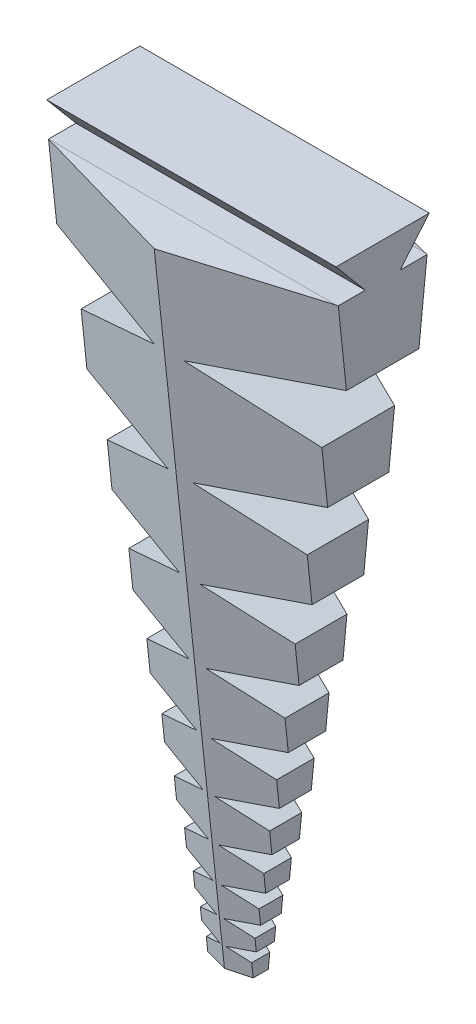
SolidWorks part; units mm, degrees
ref_plane "Front Plane" through (0, 0, 0) normal (0, 0, 1) x (1, 0, 0)
ref_plane "Top Plane" through (0, 0, 0) normal (0, 1, 0) x (1, 0, 0)
ref_plane "Right Plane" through (0, 0, 0) normal (1, 0, 0) x (0, 0, -1)
sketch "spiral_flat" plane through (0, 0, 0) normal (0, 0, 1) x (1, 0, 0)
  line L0 (3.2655, 0) -> (-3.2655, 0) construction
  line L1 (3.9293, 3.054) -> (-3.9293, 3.054) construction
  line L2 (4.728, 6.7288) -> (-4.728, 6.7288) construction
  line L3 (5.689, 11.1506) -> (-5.689, 11.1506) construction
  line L4 (6.8455, 16.4712) -> (-6.8455, 16.4712) construction
  line L5 (8.2369, 22.8733) -> (-8.2369, 22.8733) construction
  line L6 (9.9112, 30.5768) -> (-9.9112, 30.5768) construction
  line L7 (11.9259, 39.8461) -> (-11.9259, 39.8461) construction
  line L8 (14.35, 50.9996) -> (-14.35, 50.9996) construction
  line L9 (17.2669, 64.4202) -> (-17.2669, 64.4202) construction
  line L10 (20.7767, 80.5689) -> (-20.7767, 80.5689) construction
  line L11 (25, 100) -> (-25, 100) construction
  line L12 (0, -2.9617) -> (0, 103.8438) construction
  line L13 (3.2655, 0) -> (25, 100) construction
  line L14 (-3.2655, 0) -> (-25, 100) construction
  line L15 (0.3266, 0) -> (2.5, 100) construction
  line L16 (-0.3266, 0) -> (-2.5, 100) construction
  line L17 (-20.7767, 80.5689) -> (-20.7767, 100) construction
  line L18 (-17.2669, 64.4202) -> (-17.2669, 80.5689) construction
  line L19 (-14.35, 50.9996) -> (-14.35, 64.4202) construction
  line L20 (-11.9259, 39.8461) -> (-11.9259, 50.9996) construction
  line L21 (-9.9112, 30.5768) -> (-9.9112, 39.8461) construction
  line L22 (-8.2369, 22.8733) -> (-8.2369, 30.5768) construction
  line L23 (-6.8455, 16.4712) -> (-6.8455, 22.8733) construction
  line L24 (-5.689, 11.1506) -> (-5.689, 16.4712) construction
  line L25 (-4.728, 6.7288) -> (-4.728, 11.1506) construction
  line L26 (-3.9293, 3.054) -> (-3.9293, 6.7288) construction
  line L27 (-3.2655, 0) -> (-3.2655, 3.054) construction
  line L28 (20.7767, 80.5689) -> (20.7767, 100) construction
  line L29 (14.35, 50.9996) -> (14.35, 64.4202) construction
  line L30 (17.2669, 64.4202) -> (17.2669, 80.5689) construction
  line L31 (11.9259, 39.8461) -> (11.9259, 50.9996) construction
  line L32 (9.9112, 30.5768) -> (9.9112, 39.8461) construction
  line L33 (8.2369, 22.8733) -> (8.2369, 30.5768) construction
  line L34 (6.8455, 16.4712) -> (6.8455, 22.8733) construction
  line L35 (5.689, 11.1506) -> (5.689, 16.4712) construction
  line L36 (4.728, 6.7288) -> (4.728, 11.1506) construction
  line L37 (3.9293, 3.054) -> (3.9293, 6.7288) construction
  line L38 (3.2655, 0) -> (3.2655, 3.054) construction
  line L39 (-2.0777, 80.5689) -> (-17.2669, 75.0404) construction
  line L40 (-1.7267, 64.4202) -> (-17.2669, 67.1604) construction
  line L41 (-2.0777, 80.5689) -> (-20.7767, 83.866) construction
  line L42 (-1.7267, 64.4202) -> (-14.35, 59.8257) construction
  line L43 (-1.435, 50.9996) -> (-14.35, 53.2769) construction
  line L44 (-1.435, 50.9996) -> (-11.9259, 47.1812) construction
  line L45 (-1.1926, 39.8461) -> (-11.9259, 41.7387) construction
  line L46 (-1.1926, 39.8461) -> (-9.9112, 36.6728) construction
  line L47 (-0.9911, 30.5768) -> (-9.9112, 32.1496) construction
  line L48 (-0.9911, 30.5768) -> (-8.2369, 27.9395) construction
  line L49 (-0.8237, 22.8733) -> (-8.2369, 24.1805) construction
  line L50 (-0.8237, 22.8733) -> (-6.8455, 20.6816) construction
  line L51 (-0.6845, 16.4712) -> (-6.8455, 17.5576) construction
  line L52 (-0.6845, 16.4712) -> (-5.689, 14.6497) construction
  line L53 (-0.5689, 11.1506) -> (-5.689, 12.0534) construction
  line L54 (-0.5689, 11.1506) -> (-4.728, 9.6368) construction
  line L55 (-0.4728, 6.7288) -> (-4.728, 7.4791) construction
  line L56 (-0.4728, 6.7288) -> (-3.9293, 5.4708) construction
  line L57 (-0.3929, 3.054) -> (-3.9293, 3.6776) construction
  line L58 (-0.3929, 3.054) -> (-3.2655, 2.0085) construction
  line L59 (0.3929, 3.054) -> (3.2655, 2.0085) construction
  line L60 (0.3929, 3.054) -> (3.9293, 3.6776) construction
  line L61 (0.4728, 6.7288) -> (3.9293, 5.4708) construction
  line L62 (0.4728, 6.7288) -> (4.728, 7.4791) construction
  line L63 (0.5689, 11.1506) -> (4.728, 9.6368) construction
  line L64 (0.5689, 11.1506) -> (5.689, 12.0534) construction
  line L65 (0.6845, 16.4712) -> (5.689, 14.6497) construction
  line L66 (0.6845, 16.4712) -> (6.8455, 17.5576) construction
  line L67 (0.8237, 22.8733) -> (6.8455, 20.6816) construction
  line L68 (0.8237, 22.8733) -> (8.2369, 24.1805) construction
  line L69 (0.9911, 30.5768) -> (8.2369, 27.9395) construction
  line L70 (0.9911, 30.5768) -> (9.9112, 32.1496) construction
  line L71 (1.1926, 39.8461) -> (9.9112, 36.6728) construction
  line L72 (1.1926, 39.8461) -> (11.9259, 41.7387) construction
  line L73 (1.435, 50.9996) -> (11.9259, 47.1812) construction
  line L74 (1.435, 50.9996) -> (14.35, 53.2769) construction
  line L75 (1.7267, 64.4202) -> (14.35, 59.8257) construction
  line L76 (1.7267, 64.4202) -> (17.2669, 67.1604) construction
  line L77 (2.0777, 80.5689) -> (17.2669, 75.0404) construction
  line L78 (2.0777, 80.5689) -> (20.7767, 83.866) construction
  line L143 (-20.7767, 100) -> (-25, 100)
  line L144 (-25, 100) -> (-3.2655, 0)
  line L145 (-3.2655, 0) -> (-3.2655, 2.0085)
  line L146 (-0.3929, 3.054) -> (-3.9293, 3.6776)
  line L147 (-3.9293, 5.4708) -> (-0.4728, 6.7288)
  line L148 (-4.728, 7.4791) -> (-4.728, 9.6368)
  line L149 (-0.5689, 11.1506) -> (-5.689, 12.0534)
  line L150 (-5.689, 14.6497) -> (-0.6845, 16.4712)
  line L151 (-6.8455, 17.5576) -> (-6.8455, 20.6816)
  line L152 (-0.8237, 22.8733) -> (-8.2369, 24.1805)
  line L153 (-9.9112, 36.6728) -> (-1.1926, 39.8461)
  line L154 (-1.1926, 39.8461) -> (-11.9259, 41.7387)
  line L155 (-14.35, 59.8257) -> (-1.7267, 64.4202)
  line L156 (-1.7267, 64.4202) -> (-17.2669, 67.1604)
  line L157 (-17.2669, 75.0404) -> (-2.0777, 80.5689)
  line L158 (-20.7767, 83.866) -> (-20.7767, 100)
  line L159 (3.2655, 2.0085) -> (3.2655, 0)
  line L160 (0.3929, 3.054) -> (3.2655, 2.0085)
  line L161 (3.9293, 3.6776) -> (0.3929, 3.054)
  line L162 (3.9293, 5.4708) -> (3.9293, 3.6776)
  line L163 (0.4728, 6.7288) -> (3.9293, 5.4708)
  line L164 (4.728, 7.4791) -> (0.4728, 6.7288)
  line L165 (4.728, 9.6368) -> (4.728, 7.4791)
  line L166 (0.5689, 11.1506) -> (4.728, 9.6368)
  line L167 (5.689, 12.0534) -> (0.5689, 11.1506)
  line L168 (5.689, 14.6497) -> (5.689, 12.0534)
  line L169 (0.6845, 16.4712) -> (5.689, 14.6497)
  line L170 (6.8455, 17.5576) -> (0.6845, 16.4712)
  line L171 (6.8455, 20.6816) -> (6.8455, 17.5576)
  line L172 (0.8237, 22.8733) -> (6.8455, 20.6816)
  line L173 (8.2369, 24.1805) -> (0.8237, 22.8733)
  line L174 (8.2369, 27.9395) -> (8.2369, 24.1805)
  line L175 (0.9911, 30.5768) -> (8.2369, 27.9395)
  line L176 (9.9112, 32.1496) -> (0.9911, 30.5768)
  line L177 (9.9112, 36.6728) -> (9.9112, 32.1496)
  line L178 (1.1926, 39.8461) -> (9.9112, 36.6728)
  line L179 (11.9259, 41.7387) -> (1.1926, 39.8461)
  line L180 (11.9259, 47.1812) -> (11.9259, 41.7387)
  line L181 (1.435, 50.9996) -> (11.9259, 47.1812)
  line L182 (14.35, 53.2769) -> (1.435, 50.9996)
  line L183 (14.35, 59.8257) -> (14.35, 53.2769)
  line L184 (1.7267, 64.4202) -> (14.35, 59.8257)
  line L185 (17.2669, 67.1604) -> (1.7267, 64.4202)
  line L186 (17.2669, 75.0404) -> (17.2669, 67.1604)
  line L187 (2.0777, 80.5689) -> (17.2669, 75.0404)
  line L188 (20.7767, 83.866) -> (2.0777, 80.5689)
  line L189 (20.7767, 100) -> (20.7767, 83.866)
  line L190 (25, 100) -> (3.2655, 0)
  line L191 (20.7767, 100) -> (25, 100)
  line L192 (-20.7767, 83.866) -> (-2.0777, 80.5689)
  line L193 (-17.2669, 75.0404) -> (-17.2669, 67.1604)
  line L194 (-14.35, 59.8257) -> (-14.35, 53.2769)
  line L195 (-14.35, 53.2769) -> (-1.435, 50.9996)
  line L196 (-1.435, 50.9996) -> (-11.9259, 47.1812)
  line L197 (-11.9259, 47.1812) -> (-11.9259, 41.7387)
  line L198 (-9.9112, 36.6728) -> (-9.9112, 32.1496)
  line L199 (-9.9112, 32.1496) -> (-0.9911, 30.5768)
  line L200 (-0.9911, 30.5768) -> (-8.2369, 27.9395)
  line L201 (-8.2369, 27.9395) -> (-8.2369, 24.1805)
  line L202 (-6.8455, 20.6816) -> (-0.8237, 22.8733)
  line L203 (-6.8455, 17.5576) -> (-0.6845, 16.4712)
  line L204 (-5.689, 14.6497) -> (-5.689, 12.0534)
  line L205 (-0.5689, 11.1506) -> (-4.728, 9.6368)
  line L206 (-4.728, 7.4791) -> (-0.4728, 6.7288)
  line L207 (-3.9293, 5.4708) -> (-3.9293, 3.6776)
  line L208 (-0.3929, 3.054) -> (-3.2655, 2.0085)
  spline S0 degree 3 poles (0, 0) (0, 1.018) (0, 3.261) (0, 6.9778) (0, 11.4502) (0, 16.8317) (0, 23.3071) (0, 31.0987) (0, 40.4742) (0, 51.7553) (0, 65.3296) (0, 81.663) (0, 93.523) (0, 100) knots 0 0 0 0 0.03054 0.067288 0.111506 0.164712 0.228733 0.305768 0.398461 0.509996 0.644202 0.805689 1 1 1 1
  point P39 (0, 3.054)
  point P40 (0, 6.7288)
  point P41 (0, 11.1506)
  point P42 (0, 16.4712)
  point P43 (0, 22.8733)
  point P44 (0, 30.5768)
  point P45 (0, 39.8461)
  point P46 (0, 50.9996)
  point P47 (0, 64.4202)
  point P48 (0, 80.5689)
  point P49 (-0.3266, 0)
  point P50 (-0.3929, 3.054)
  point P51 (-0.4728, 6.7288)
  point P52 (-0.5689, 11.1506)
  point P53 (-0.6845, 16.4712)
  point P54 (-0.8237, 22.8733)
  point P55 (-0.9911, 30.5768)
  point P56 (-1.1926, 39.8461)
  point P57 (-1.435, 50.9996)
  point P58 (-1.7267, 64.4202)
  point P59 (-2.0777, 80.5689)
  point P60 (-2.5, 100)
  point P61 (0.3266, 0)
  point P62 (0.3929, 3.054)
  point P63 (0.4728, 6.7288)
  point P64 (0.5689, 11.1506)
  point P65 (0.6845, 16.4712)
  point P66 (0.8237, 22.8733)
  point P67 (0.9911, 30.5768)
  point P68 (1.1926, 39.8461)
  point P69 (1.435, 50.9996)
  point P70 (1.7267, 64.4202)
  point P71 (2.0777, 80.5689)
  point P72 (2.5, 100)
  dimension "D1" = 100
  dimension "D3" = 7.8586
  dimension "D2" = 6.531
  dimension "D4" = 9.456
  dimension "D5" = 11.3781
  dimension "D6" = 13.6909
  dimension "D7" = 16.4738
  dimension "D8" = 19.8224
  dimension "D9" = 23.8517
  dimension "D10" = 28.7
  dimension "D11" = 34.5338
  dimension "D12" = 41.5535
  dimension "D13" = 50
  dimension "D14" = 0.6531
  dimension "D15" = 0.7859
  dimension "D16" = 0.9456
  dimension "D17" = 1.1378
  dimension "D18" = 1.3691
  dimension "D19" = 1.6474
  dimension "D20" = 1.9822
  dimension "D21" = 2.3852
  dimension "D22" = 2.87
  dimension "D23" = 3.4534
  dimension "D24" = 4.1553
  dimension "D25" = 5
  dimension "D26" = 20
  dimension "D27" = 10
  dimension "D28" = 10
  dimension "D29" = 20
  dimension "D30" = 10
  dimension "D31" = 20
  dimension "D32" = 10
  dimension "D33" = 20
  dimension "D34" = 10
  dimension "D35" = 20
  dimension "D36" = 10
  dimension "D37" = 20
  dimension "D38" = 10
  dimension "D39" = 20
  dimension "D40" = 10
  dimension "D41" = 20
  dimension "D42" = 10
  dimension "D43" = 20
  dimension "D44" = 10
  dimension "D45" = 20
sketch "Sketch2" plane through (0, 0, 0) normal (0, 1, 0) x (1, 0, 0)
  line L0 (3.2655, 0) -> (-3.2384, 0) construction
  line L1 (0.0136, -1.9593) -> (0.0136, 1.9593) construction
  line L2 (3.2655, -1.9593) -> (3.2655, 1.9593) construction
  line L3 (-3.2384, -1.9593) -> (-3.2384, 1.9593) construction
  line L4 (3.2655, 1.9593) -> (-3.2384, 1.9593) construction
  line L5 (0.0136, 1.9593) -> (3.2655, 1.088) construction
  line L6 (3.2655, -1.9593) -> (-3.2384, -1.9593) construction
  line L7 (0.0136, -1.9593) -> (3.2655, -1.088) construction
  line L8 (0.0136, -1.9593) -> (-3.2384, -1.088) construction
  line L9 (0.0136, 1.9593) -> (-3.2384, 1.088) construction
  line L10 (0.0136, 1.9593) -> (-3.2384, 1.088)
  line L11 (-3.2384, 1.088) -> (-3.2384, -1.088)
  line L12 (-3.2384, -1.088) -> (0.0136, -1.9593)
  line L13 (0.0136, -1.9593) -> (3.2655, -1.088)
  line L14 (3.2655, -1.088) -> (3.2655, 1.088)
  line L15 (3.2655, 1.088) -> (0.0136, 1.9593)
  point P7 (0.0136, 0)
  dimension "D1" = 3.9186
  dimension "D2" = 15
ref_plane "Plane1" through (0, 100, 0) normal (0, 1, 0) x (1, 0, 0)
sketch "Sketch3" plane through (0, 100, 0) normal (0, 1, 0) x (1, 0, 0)
  line L0 (-25, 0) -> (24.7531, 0) construction
  line L1 (20.7767, 0) -> (-20.7767, 0) construction
  line L2 (-0.1234, -12.5) -> (-0.1234, 12.5) construction
  line L5 (24.7531, 12.5) -> (-25, 12.5) construction
  line L6 (-0.1234, 12.5) -> (-25, 5.8343) construction
  line L7 (24.7531, -12.5) -> (-25, -12.5) construction
  line L8 (-0.1234, -12.5) -> (-25, -5.8343) construction
  line L9 (-0.1234, -12.5) -> (24.7531, -5.8343) construction
  line L10 (-0.1234, 12.5) -> (24.7531, 5.8343) construction
  line L11 (-3.2655, 0) -> (-25, 0) construction
  line L12 (-25, -12.5) -> (-25, 12.5) construction
  line L15 (24.7531, -12.5) -> (24.7531, 12.5) construction
  line L16 (-0.1234, 12.5) -> (-25, 5.8343)
  line L17 (-25, 5.8343) -> (-25, -5.8343)
  line L18 (-25, -5.8343) -> (-0.1234, -12.5)
  line L19 (-0.1234, -12.5) -> (24.7531, -5.8343)
  line L20 (24.7531, -5.8343) -> (24.7531, 5.8343)
  line L21 (24.7531, 5.8343) -> (-0.1234, 12.5)
  point P8 (-0.1234, 0)
  point P9 (0, 0)
  point P16 (-25, 5.8343)
  dimension "D1" = 25
  dimension "D2" = 15
loft "Loft1" add profiles "Sketch2", "Sketch3"
extrude "Cut-Extrude2" cut sketch "spiral_flat" against normal through all both and the other way through all contours L192 L157 L193 L156 L155 L194 L195 L196 L197 L154 L153 L198 L199 L200 L201 L152 L202 L151 L203 L150 L204 L149 L205 L148 L206 L147 L207 L146 L208 L145 L144 L143 L158 | L188 L187 L186 L185 L184 L183 L182 L181 L180 L179 L178 L177 L176 L175 L174 L173 L172 L171 L170 L169 L168 L167 L166 L165 L164 L163 L162 L161 L160 L159 L190 L191 L189
ref_plane "Plane3" through (-20.7767, 0, 0) normal (-1, 0, 0) x (0, 0, 1)
sketch "Sketch6" plane through (-20.7767, 0, 0) normal (-1, 0, 0) x (0, 0, 1)
  line L0 (0, 100) -> (0, 83.866) construction
  line L1 (22.8545, 100) -> (-22.8545, 100) construction
  line L2 (-5.2594, 83.866) -> (5.2594, 83.866) construction
  line L3 (24.3259, 95) -> (-24.3259, 95) construction
  line L4 (2.5, 95) -> (6.6955, 100) construction
  line L5 (-2.5, 95) -> (-6.6955, 100) construction
  line L6 (2.5, 95) -> (6.6955, 100)
  line L7 (6.6955, 100) -> (6.966, 100)
  line L8 (6.966, 100) -> (5.2594, 83.866) construction
  line L9 (6.966, 100) -> (6.4371, 95)
  line L10 (6.4371, 95) -> (2.5, 95)
  line L11 (-2.5, 95) -> (-6.6955, 100)
  line L12 (-6.6955, 100) -> (-6.966, 100)
  line L13 (-6.966, 100) -> (-6.4371, 95)
  line L14 (-5.2594, 83.866) -> (-6.966, 100) construction
  line L15 (-6.4371, 95) -> (-2.5, 95)
  point P6 (0, 95)
  point P7 (-2.5, 95)
  point P10 (0, 95)
  point P11 (2.5, 95)
  dimension "D1" = 5
  dimension "D2" = 5
  dimension "D3" = 50
extrude "Cut-Extrude3" cut sketch "Sketch6" against normal through all and the other way through all contours L11 L12 L13 L15 | L10 L6 L7 L9
sketch "Sketch9" plane through (0, 0.3778, -3.5715) normal (0, 0.1052, -0.9945) x (-1, 0, 0)
  line L0 (-20.5436, 95.1501) -> (-20.5299, 100.178)
  line L1 (-20.5299, 100.178) -> (20.7767, 100.178)
  line L2 (20.7767, 100.178) -> (20.7767, 95.1501)
  line L3 (20.7767, 95.1501) -> (-20.5436, 95.1501)
extrude "Cut-Extrude5" cut sketch "Sketch9" against normal blind 10
sketch "Sketch10" plane through (0, 0.3778, 3.5715) normal (0, 0.1052, 0.9945) x (1, 0, 0)
  line L0 (20.5299, 100.178) -> (20.5436, 95.1501)
  line L1 (20.5436, 95.1501) -> (-20.7767, 95.1501)
  line L2 (-20.7767, 95.1501) -> (-20.7767, 100.178)
  line L3 (-20.7767, 100.178) -> (20.5299, 100.178)
extrude "Cut-Extrude6" cut sketch "Sketch10" against normal blind 10
sketch "Sketch11" plane through (0, 100, 0) normal (0, 1, 0) x (1, 0, 0)
  line L0 (-0.1234, -12.5) -> (20.5299, -6.966)
  line L1 (24.7531, -12.5) -> (-25, -12.5) construction
  line L2 (20.5299, -6.966) -> (-20.7767, -6.966)
  line L3 (-25, -5.8343) -> (-0.1234, -12.5) construction
  line L4 (-20.7767, 7.365) -> (-20.7767, -7.365) construction
  line L5 (-20.7767, -6.966) -> (-0.1234, -12.5)
  line L6 (-0.1234, 12.5) -> (-20.7767, 6.966)
  line L7 (-0.1234, 12.5) -> (-25, 5.8343) construction
  line L8 (20.5299, 6.966) -> (-20.7767, 6.966) construction
  line L9 (-20.7767, 6.966) -> (20.5299, 6.966)
  line L10 (20.5299, 6.966) -> (-0.1234, 12.5)
extrude "Cut-Extrude7" cut sketch "Sketch11" against normal blind 5
